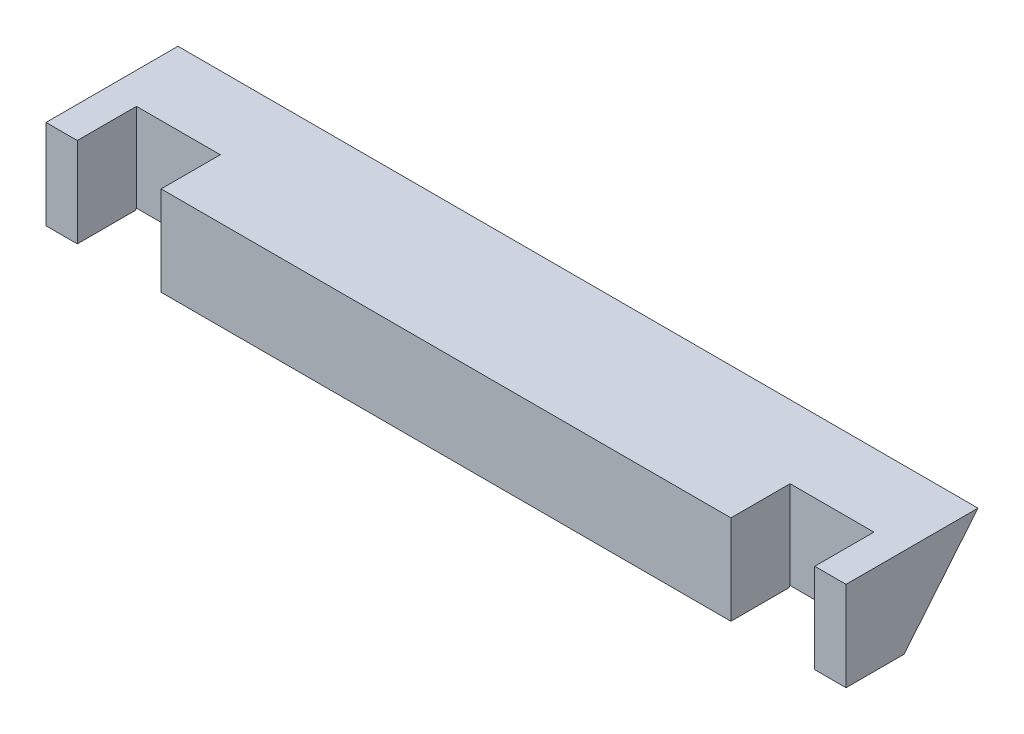
SolidWorks part; units mm, degrees
ref_plane "前视基准面" through (0, 0, 0) normal (0, 0, 1) x (1, 0, 0)
ref_plane "上视基准面" through (0, 0, 0) normal (0, 1, 0) x (1, 0, 0)
ref_plane "右视基准面" through (0, 0, 0) normal (1, 0, 0) x (0, 0, -1)
sketch "草图1" plane through (0, 0, 0) normal (1, 0, 0) x (0, 0, -1)
  line L0 (51.7112, 31.8223) -> (-12.5088, 31.8223)
  line L1 (-12.5088, 31.8223) -> (-12.5088, -45.9877)
  line L2 (-12.5088, -45.9877) -> (51.7112, 31.8223)
extrude "凸台-拉伸1" add sketch "草图1" along normal blind 695
sketch "草图2" plane through (0, 0, 12.5088) normal (0, 0, 1) x (1, 0, 0)
  line L1 (0, 31.8223) -> (695, 31.8223)
  line L2 (0, 31.8223) -> (0, -45.9877)
  line L3 (0, -45.9877) -> (695, -45.9877)
  line L4 (695, 31.8223) -> (695, -45.9877)
extrude "凸台-拉伸2" add sketch "草图2" along normal blind 50.41
sketch "草图3" plane through (0, 31.8223, 0) normal (0, 1, 0) x (1, 0, 0)
  line L0 (0, 51.7112) -> (0, -62.9188) construction
  line L1 (0, -5.6038) -> (27.19, -5.6038)
  line L2 (0, -5.6038) -> (0, -62.9188)
  line L3 (0, -62.9188) -> (27.19, -62.9188)
  line L4 (27.19, -5.6038) -> (27.19, -62.9188)
  line L5 (695, -62.9188) -> (0, -62.9188) construction
sketch "草图4" plane through (0, 31.8223, 0) normal (0, 1, 0) x (1, 0, 0)
  line L1 (695, -62.9188) -> (667.81, -62.9188)
  line L2 (695, -62.9188) -> (695, -11.5188)
  line L3 (695, -11.5188) -> (667.81, -11.5188)
  line L4 (667.81, -62.9188) -> (667.81, -11.5188)
  line L5 (27.19, -62.9188) -> (100.01, -62.9188)
  line L6 (27.19, -62.9188) -> (27.19, -11.5188)
  line L7 (27.19, -11.5188) -> (100.01, -11.5188)
  line L8 (100.01, -62.9188) -> (100.01, -11.5188)
  dimension "D1" = 72.82
  dimension "D2" = 51.4
  dimension "D3" = 27.19
sketch "草图9" plane through (0, 31.8223, 0) normal (0, 1, 0) x (1, 0, 0)
  line L0 (27.19, -11.5188) -> (100.01, -11.5188) construction
  line L3 (27.19, -62.9188) -> (100.01, -62.9188) construction
  line L6 (100.01, -62.9188) -> (27.19, -62.9188)
  line L7 (100.01, -62.9188) -> (100.01, -11.5188)
  line L8 (100.01, -11.5188) -> (27.19, -11.5188)
  line L9 (27.19, -62.9188) -> (27.19, -11.5188)
  point P2 (63.6, -62.9188)
  point P9 (63.6, -11.5188)
extrude "切除-拉伸3" cut sketch "草图9" against normal blind 1000
sketch "草图10" plane through (0, 31.8223, 0) normal (0, 1, 0) x (1, 0, 0)
  line L1 (667.81, -62.9188) -> (594.99, -62.9188)
  line L2 (667.81, -62.9188) -> (667.81, -11.5188)
  line L3 (667.81, -11.5188) -> (594.99, -11.5188)
  line L4 (594.99, -62.9188) -> (594.99, -11.5188)
extrude "切除-拉伸4" cut sketch "草图10" against normal blind 1000
